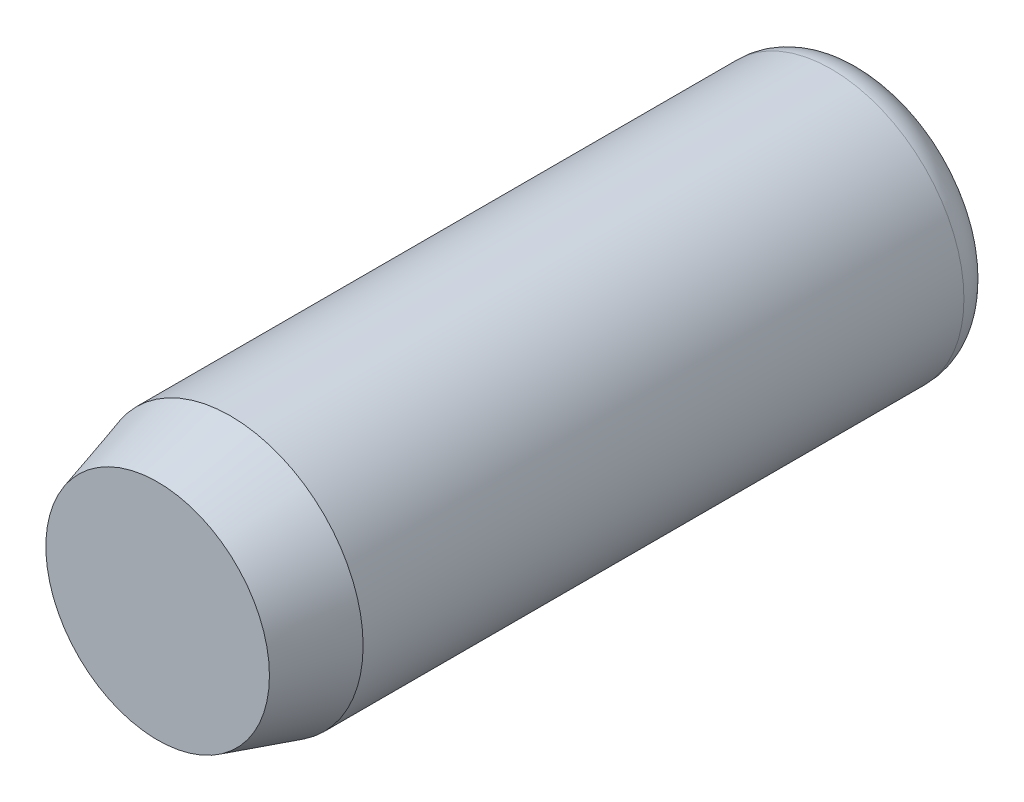
SolidWorks part; units mm, degrees
ref_plane "Front Plane" through (0, 0, 0) normal (0, 0, 1) x (1, 0, 0)
ref_plane "Top Plane" through (0, 0, 0) normal (0, 1, 0) x (1, 0, 0)
ref_plane "Right Plane" through (0, 0, 0) normal (1, 0, 0) x (0, 0, -1)
sketch "Sketch1" plane through (0, 0, 0) normal (0, 0, 1) x (1, 0, 0)
  circle A0 centre (0, 0) radius 1.1906
  point P3 (0, 1.1906)
  dimension "Diameter" = 2.3813
sketch "Sketch2" plane through (0, 0, 0) normal (1, 0, 0) x (0, 0, -1)
  line L0 (-3.175, 0) -> (3.175, 0) construction
  line L1 (-3.175, 0) -> (-3.175, 1.1906)
  line L2 (-3.175, 1.0033) -> (-2.5217, 1.1906)
  line L3 (-3.175, 1.1906) -> (3.175, 1.1906)
  line L4 (3.175, 1.1906) -> (3.175, 0)
  arc A0 (3.175, 0.8858) -> (2.8702, 1.1906) centre (2.8702, 0.8858) ccw
  point P11 (2.3876, 1.1906)
  dimension "Crown Radius" = 0.3048
  dimension "Length" = 6.35
  dimension "Point Diameter" = 2.0066
  dimension "Chamfer Angle" = 16
  dimension "Crown Height" = 0.7874
sketch "Sketch3" plane through (0, 0, 0) normal (1, 0, 0) x (0, 0, -1)
  line L0 (3.175, 1.1906) -> (3.175, 0) construction
  line L1 (-3.175, 1.1906) -> (3.175, 1.1906) construction
  line L2 (-3.175, 0) -> (-3.175, 1.1906) construction
  line L3 (3.175, 0.8858) -> (3.175, 0)
  line L4 (-2.5217, 1.1906) -> (2.8702, 1.1906)
  line L5 (-3.175, 0) -> (-3.175, 1.0033)
  line L6 (-3.175, 0) -> (3.175, 0) construction
  line L7 (-3.175, 0) -> (3.175, 0)
  line L8 (-3.175, 1.0033) -> (-2.5217, 1.1906) construction
  line L9 (-3.175, 1.0033) -> (-2.5217, 1.1906)
  arc A0 (3.175, 0.8858) -> (2.8702, 1.1906) centre (2.8702, 0.8858) ccw construction
  arc A1 (3.175, 0.8858) -> (2.8702, 1.1906) centre (2.8702, 0.8858) ccw
revolve "Revolve1" add sketch "Sketch3" angle 360 about L0
